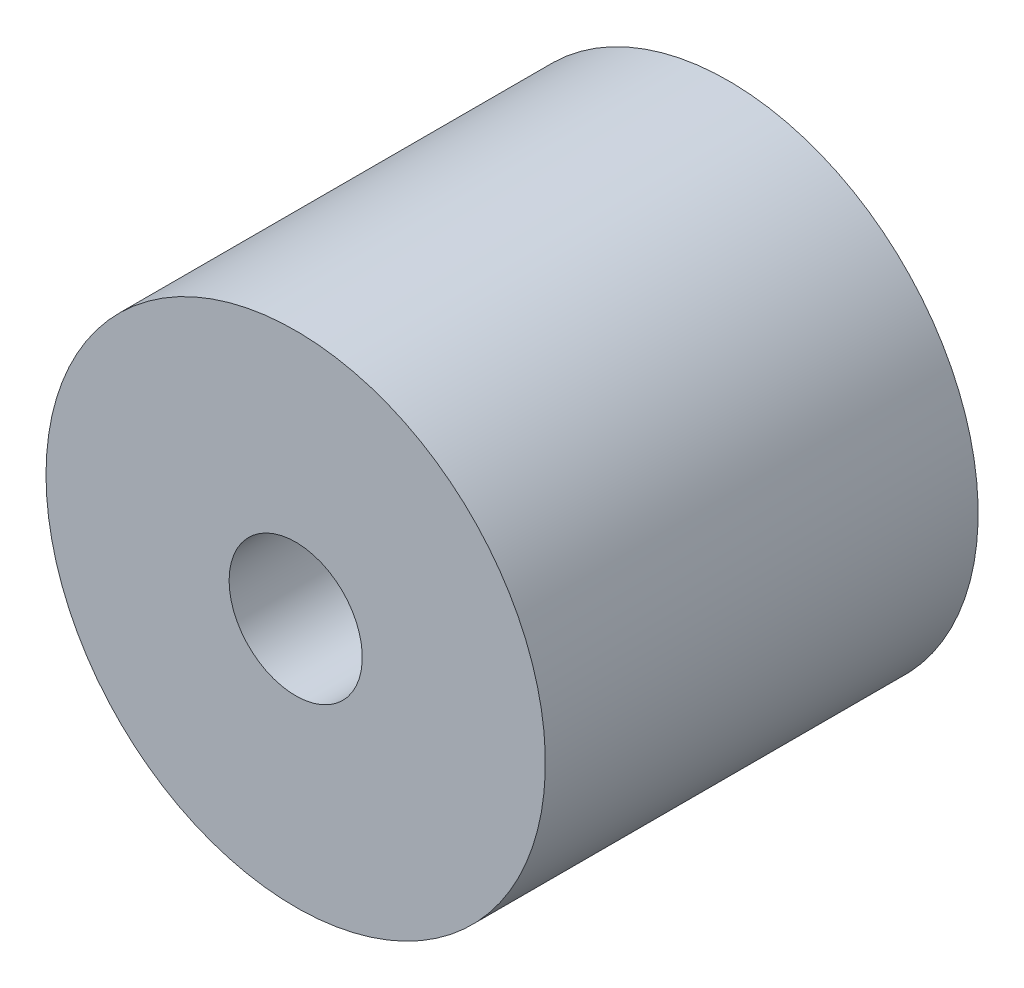
SolidWorks part; units mm, degrees
ref_plane "Front Plane" through (0, 0, 0) normal (0, 0, 1) x (1, 0, 0)
ref_plane "Top Plane" through (0, 0, 0) normal (0, 1, 0) x (1, 0, 0)
ref_plane "Right Plane" through (0, 0, 0) normal (1, 0, 0) x (0, 0, -1)
sketch "Sketch1" plane through (0, 0, 0) normal (0, 0, 1) x (1, 0, 0)
  circle A0 centre (0, 0) radius 15
  circle A1 centre (0, 0) radius 4
extrude "Boss-Extrude1" add sketch "Sketch1" along normal blind 26
